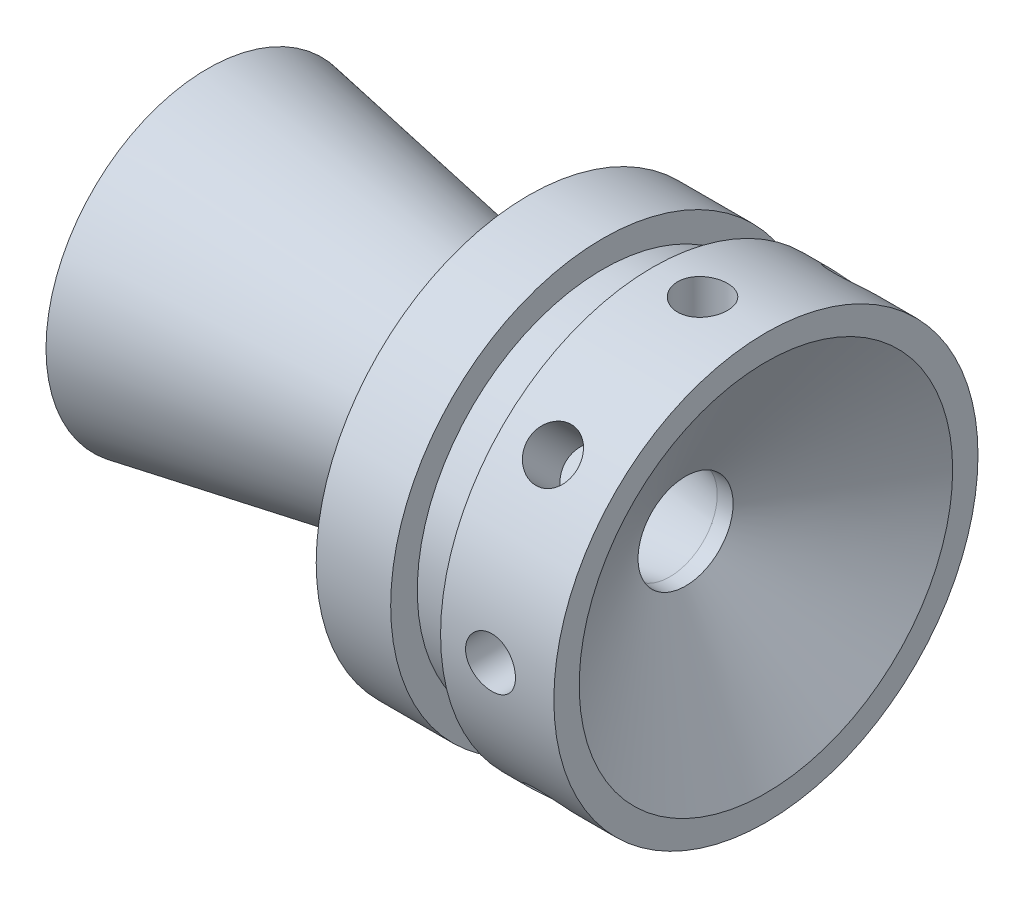
SolidWorks part; units mm, degrees
ref_plane "Front Plane" through (0, 0, 0) normal (0, 0, 1) x (1, 0, 0)
ref_plane "Top Plane" through (0, 0, 0) normal (0, 1, 0) x (1, 0, 0)
ref_plane "Right Plane" through (0, 0, 0) normal (1, 0, 0) x (0, 0, -1)
sketch "Sketch1" plane through (0, 0, 0) normal (0, 0, 1) x (1, 0, 0)
  line L0 (0, 0) -> (-1176.051, 0) construction
  line L1 (0, 0) -> (0, -1176.051) construction
  line L2 (0, 8.4213) -> (0, 17)
  line L3 (0, 17) -> (5.969, 17)
  line L4 (5.969, 17) -> (5.969, 14.8664)
  line L5 (5.969, 14.8664) -> (9.969, 14.8664)
  line L6 (9.969, 14.8664) -> (9.969, 17)
  line L7 (9.969, 17) -> (19.05, 17)
  line L10 (19.05, 17) -> (19.05, 14.968)
  line L11 (19.05, 14.968) -> (12.6079, 3.81)
  line L12 (12.6079, 3.81) -> (11.3379, 3.81)
  line L13 (11.3379, 3.81) -> (-25.7063, 11.684)
  line L14 (-25.7063, 11.684) -> (-25.7063, 12.954)
  line L15 (-25.7063, 12.954) -> (0, 8.4213)
  dimension "D1" = 17
  dimension "D2" = 5.969
  dimension "D3" = 2.1336
  dimension "D4" = 4
  dimension "D5" = 19.05
  dimension "D8" = 2.032
  dimension "D9" = 150
  dimension "D10" = 1.27
  dimension "D11" = 80
  dimension "D12" = 168
  dimension "D13" = 3.81
  dimension "D14" = 1.27
  dimension "D15" = 11.684
revolve "Revolve1" add sketch "Sketch1" angle 360 about L0
ref_plane "Plane1" through (0, 0, 17.78) normal (0, 0, 1) x (1, 0, 0)
sketch "Sketch2" plane through (0, 0, 17.78) normal (0, 0, 1) x (1, 0, 0)
  line L0 (19.05, 0) -> (12.6079, 0) construction
  line L1 (-25.7063, 0) -> (0, 0) construction
  line L2 (19.05, -17) -> (19.05, 17) construction
  circle A0 centre (13.97, 0) radius 2
  dimension "D1" = 4
  dimension "D2" = 5.08
extrude "Cut-Extrude1" cut sketch "Sketch2" against normal blind 5.08
pattern_circular "CirPattern1" count 8 over 360 about axis through (0, 0, 0) along (1, 0, 0) of "Cut-Extrude1"
